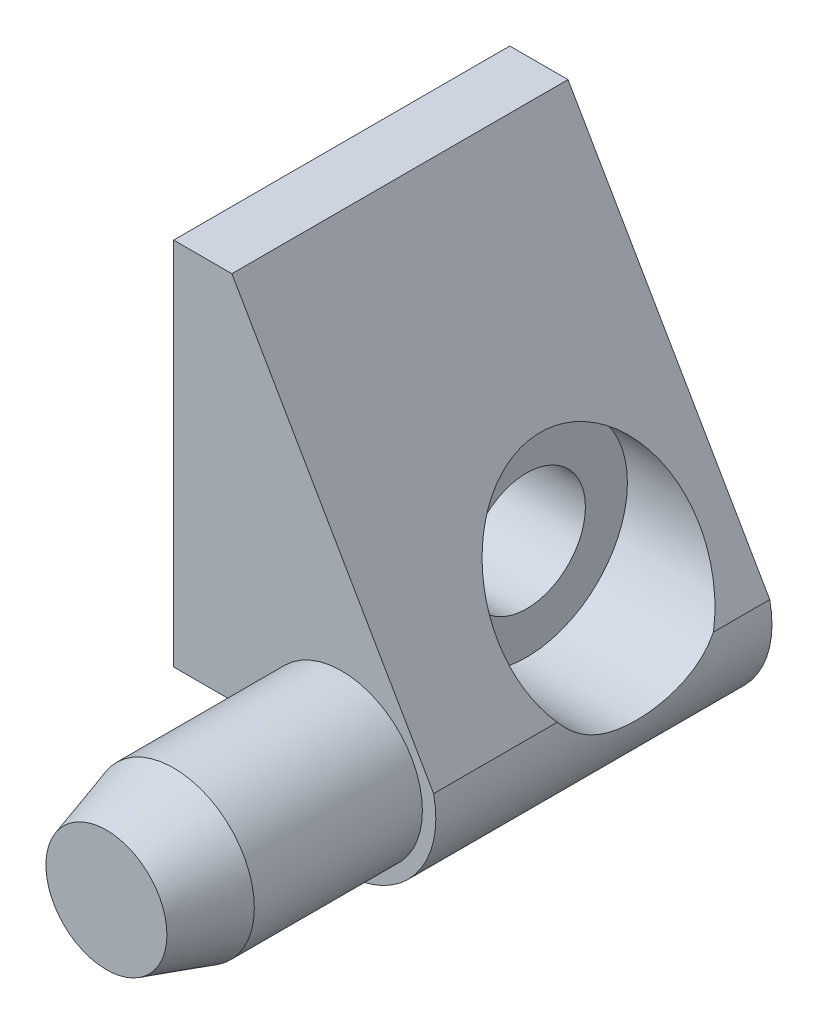
SolidWorks part; units mm, degrees
ref_plane "Plan de face" through (0, 0, 0) normal (0, 0, 1) x (1, 0, 0)
ref_plane "Plan de dessus" through (0, 0, 0) normal (0, 1, 0) x (1, 0, 0)
ref_plane "Plan de droite" through (0, 0, 0) normal (1, 0, 0) x (0, 0, -1)
ref_plane "Plan4" through (0, 0, 0) normal (0, 0, -1) x (-1, 0, 0)
sketch "Esquisse1" plane through (0, 0, 0) normal (0, 0, -1) x (-1, 0, 0)
  line L0 (2.8, 6) -> (5, 6)
  line L1 (5, 6) -> (5, 17)
  line L2 (5, 17) -> (3.2679, 17)
  line L3 (3.2679, 17) -> (-2.734, 6.6043)
  arc A0 (-2.734, 6.6043) -> (2.8, 6) centre (0, 6) ccw
extrude "Boss.-Extru.1" add sketch "Esquisse1" against normal blind 10
ref_plane "Plan5" through (0, 6, 0) normal (0, 1, 0) x (1, 0, 0)
sketch "Esquisse2" plane through (0, 6, 0) normal (0, 1, 0) x (1, 0, 0)
  line L0 (2.4, -10) -> (0, -10)
  line L1 (0, -10) -> (0, -17)
  line L2 (0, -17) -> (1.8, -17)
  line L3 (1.8, -17) -> (2.4, -15)
  line L4 (2.4, -15) -> (2.4, -10)
  line L5 (0, -10) -> (0, -17) construction
revolve "Révolution1" add sketch "Esquisse2" angle 360 about L5
ref_plane "Plan6" through (2.8, 0, 0) normal (1, 0, 0) x (0, 0, -1)
hole_wizard "Chambrage pour vis à tête courte bombée à empreinte cruciforme #51" positions "Esquisse4" profile "Esquisse3" counterbore size "#5" standard "Ansi Inch"
sketch "Esquisse4" plane through (2.8, 0, 0) normal (1, 0, 0) x (0, 0, -1)
  point P0 (-4, 8.5)
sketch "Esquisse3" plane through (2.8, 8.5, 4) normal (0, 1, 0) x (0, 0, -1)
  line L0 (0, 0) -> (0, 7.8)
  line L1 (0, 7.8) -> (1.75, 7.8)
  line L3 (1.75, 7.8) -> (1.75, 3.3)
  line L4 (1.75, 3.3) -> (3, 3.3)
  line L5 (3, 3.3) -> (3, 0)
  line L7 (3, 0) -> (0, 0)
  line L11 (0, -6.35) -> (0, 107.95) construction
  dimension "Diamètre du perçage jusqu'au prochain" = 3.5
  dimension "Profondeur du perçage jusqu'au prochain" = 7.8
  dimension "Diamètre du chambrage" = 6
  dimension "Profondeur du chambrage" = 3.3
